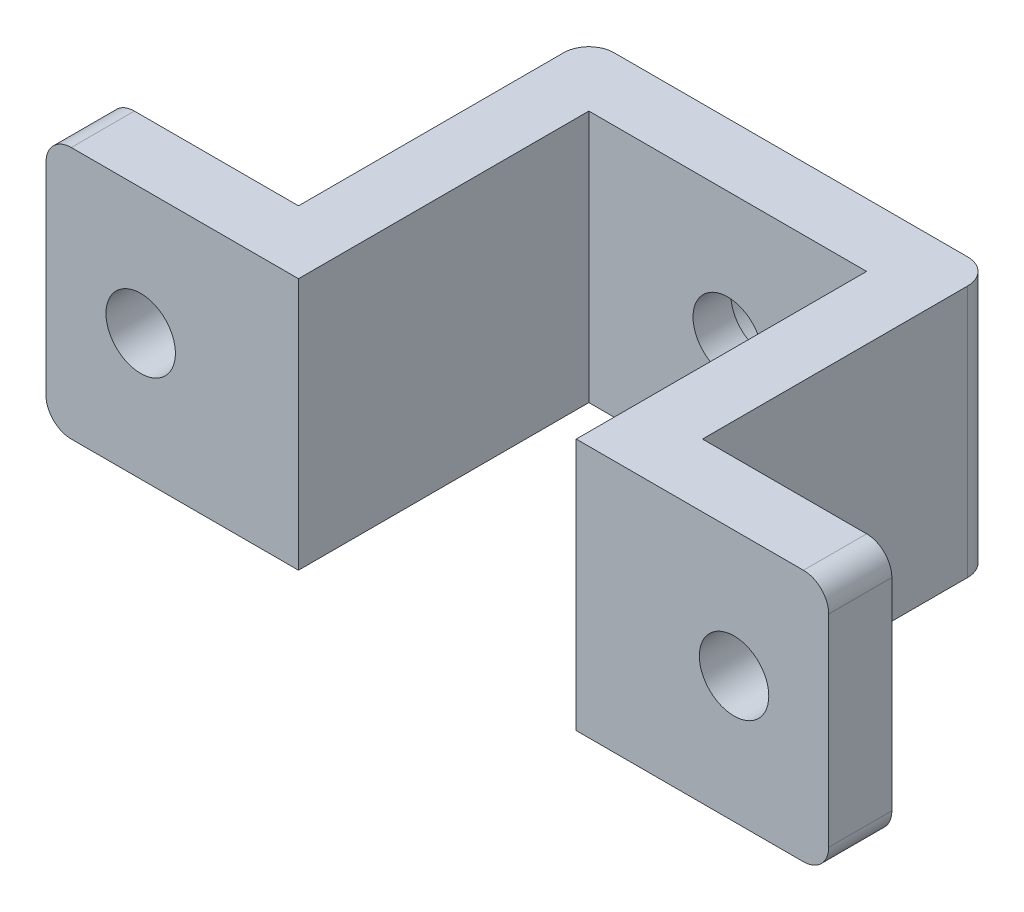
SolidWorks part; units mm, degrees
ref_plane "前视基准面" through (0, 0, 0) normal (0, 0, 1) x (1, 0, 0)
ref_plane "上视基准面" through (0, 0, 0) normal (0, 1, 0) x (1, 0, 0)
ref_plane "右视基准面" through (0, 0, 0) normal (1, 0, 0) x (0, 0, -1)
sketch "草图1" plane through (0, 0, 0) normal (0, 1, 0) x (1, 0, 0)
  line L1 (-12.058, 6.2222) -> (19.942, 6.2222)
  line L2 (-12.058, 6.2222) -> (-12.058, -21.7778)
  line L3 (-12.058, -21.7778) -> (-7.058, -21.7778)
  line L4 (19.942, 6.2222) -> (19.942, -21.7778)
  line L5 (-12.058, 6.2222) -> (3.942, -7.7778) construction
  line L6 (-12.058, -21.7778) -> (-7.058, -17.4028) construction
  line L7 (-7.058, 1.2222) -> (14.942, 1.2222)
  line L8 (14.942, 1.2222) -> (14.942, -16.7778)
  line L10 (-7.058, 1.2222) -> (-7.058, -16.7778)
  line L11 (-7.058, -16.7778) -> (-7.058, -21.7778)
  line L12 (14.942, -16.7778) -> (14.942, -21.7778)
  line L14 (-7.058, -16.7778) -> (14.942, -16.7778) construction
  line L15 (14.942, -21.7778) -> (19.942, -21.7778)
  line L16 (-12.058, -21.7778) -> (19.942, -21.7778) construction
  line L17 (3.942, -7.7778) -> (19.942, 6.2222) construction
  line L18 (14.942, -17.4028) -> (19.942, -21.7778) construction
  point P4 (3.942, -7.7778)
  dimension "D1" = 32
  dimension "D2" = 28
  dimension "D3" = 5
extrude "凸台-拉伸1" add sketch "草图1" along normal blind 20
sketch "草图2" plane through (0, 0, -6.2222) normal (0, 0, -1) x (-1, 0, 0)
  line L0 (-19.942, 10) -> (12.058, 10) construction
  line L1 (-19.942, 20) -> (-19.942, 0) construction
  line L2 (12.058, 20) -> (12.058, 0) construction
  circle A0 centre (-3.942, 10) radius 2.75
  dimension "D1" = 5.5
extrude "切除-拉伸1" cut sketch "草图2" against normal through all
sketch "草图3" plane through (-12.058, 0, 0) normal (-1, 0, 0) x (0, 0, 1)
  line L0 (16.7778, 0) -> (16.7778, 20)
  line L1 (-6.2222, 0) -> (21.7778, 0) construction
  line L2 (-6.2222, 20) -> (21.7778, 20) construction
  line L3 (16.7778, 20) -> (21.7778, 20)
  line L4 (21.7778, 20) -> (21.7778, 0)
  line L5 (21.7778, 0) -> (16.7778, 0)
  dimension "D1" = 5
extrude "凸台-拉伸2" add sketch "草图3" along normal blind 15
ref_plane "基准面1" through (3.942, 0, 0) normal (1, 0, 0) x (0, 0, -1)
sketch "草图4" plane through (0, 0, 16.7778) normal (0, 0, -1) x (-1, 0, 0)
  line L0 (19.558, 20) -> (19.558, 0) construction
  line L1 (27.058, 20) -> (12.058, 20) construction
  line L2 (27.058, 0) -> (12.058, 0) construction
  circle A0 centre (19.558, 10) radius 2.75
  dimension "D1" = 5.5
extrude "切除-拉伸2" cut sketch "草图4" against normal through all
ref_plane "基准面2" through (3.942, 0, 0) normal (-1, 0, 0) x (0, 0, 1)
ref_plane "基准面3" through (3.942, 0, 0) normal (-1, 0, 0) x (0, 0, 1)
ref_plane "基准面4" through (3.942, 0, 0) normal (-1, 0, 0) x (0, 0, 1)
mirror "镜向5" about plane through (3.942, 0, 0) normal (-1, 0, 0) of "切除-拉伸2", "凸台-拉伸2"
fillet "圆角1" radius 2 6 edges at (34.942, 0, 19.2778) (34.942, 20, 19.2778) (19.942, 10, -6.2222) (-27.058, 0, 19.2778) (-27.058, 20, 19.2778) (-12.058, 10, -6.2222)
sketch "草图5" plane through (0, 0, -6.2222) normal (0, 0, -1) x (-1, 0, 0)
  circle A1 centre (-3.942, 10) radius 4
  dimension "D1" = 8
extrude "切除-拉伸3" cut sketch "草图5" against normal blind 2
